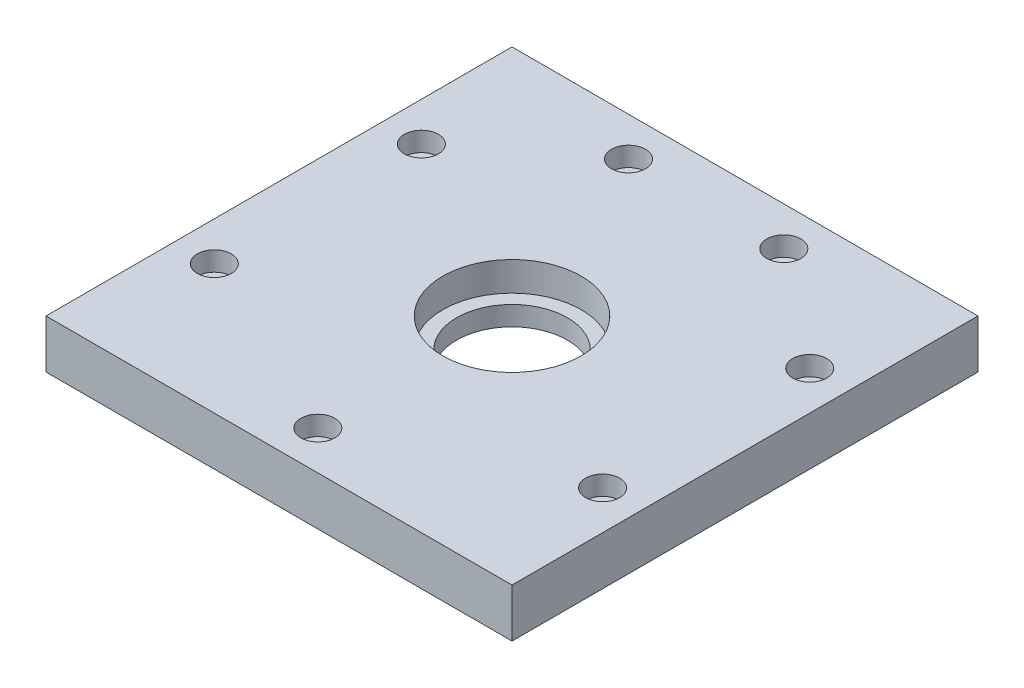
SolidWorks part; units mm, degrees
material "6061-O (SS)"
ref_plane "Front Plane" through (0, 0, 0) normal (0, 0, 1) x (1, 0, 0)
ref_plane "Top Plane" through (0, 0, 0) normal (0, 1, 0) x (1, 0, 0)
ref_plane "Right Plane" through (0, 0, 0) normal (1, 0, 0) x (0, 0, -1)
sketch "Sketch1" plane through (0, 0, 0) normal (0, 0, 1) x (1, 0, 0)
  line L7 (-76.2, -7.9375) -> (76.2, -7.9375)
  line L8 (-76.2, -7.9375) -> (-76.2, 7.9375)
  line L9 (-76.2, 7.9375) -> (76.2, 7.9375)
  line L10 (76.2, -7.9375) -> (76.2, 7.9375)
  line L11 (-76.2, -7.9375) -> (76.2, 7.9375) construction
  line L12 (-76.2, 7.9375) -> (76.2, -7.9375) construction
  point P4 (0, 0)
  point P14 (0, 0)
  dimension "Thickness" = 15.875
  dimension "Width" = 152.4
sketch "Sketch2" plane through (0, 0, 0) normal (0, 1, 0) x (0, 0, -1)
  line L0 (76.2, 76.2) -> (-76.2, 76.2) construction
  point P4 (0, 76.2)
  dimension "Length" = 152.4
sketch "Sketch3" plane through (0, 0, 0) normal (0, 0, 1) x (1, 0, 0)
  line L6 (-76.2, 7.9375) -> (76.2, 7.9375)
  line L7 (76.2, 7.9375) -> (76.2, -7.9375)
  line L8 (76.2, -7.9375) -> (-76.2, -7.9375)
  line L9 (-76.2, -7.9375) -> (-76.2, 7.9375)
extrude "Boss-Extrude1" add sketch "Sketch3" along normal mid plane 152.4
sketch "Sketch4" plane through (0, 7.9375, 0) normal (0, 1, 0) x (1, 0, 0)
  circle A0 centre (0, 0) radius 22.6219
  dimension "D1" = 45.2437
extrude "Cut-Extrude1" cut sketch "Sketch4" against normal blind 9.525
sketch "Sketch5" plane through (0, -1.5875, 0) normal (0, 1, 0) x (1, 0, 0)
  circle A0 centre (0, 0) radius 18.0975
  dimension "D1" = 36.195
extrude "Cut-Extrude2" cut sketch "Sketch5" against normal through all
sketch "Sketch6" plane through (0, 7.9375, 0) normal (0, 1, 0) x (1, 0, 0)
  line L2 (76.2, -76.2) -> (76.2, 76.2) construction
  line L3 (76.2, 76.2) -> (-76.2, 76.2) construction
  line L4 (-76.2, -76.2) -> (-76.2, 76.2) construction
  line L5 (76.2, -76.2) -> (-76.2, -76.2) construction
  point P0 (-25.4, 63.5)
  point P1 (-63.5, -33.8667)
  point P2 (-63.5, 33.8667)
  point P3 (25.4, 63.5)
  point P4 (63.5, 33.8667)
  point P5 (63.5, -33.8667)
  point P6 (0, -63.5)
  dimension "D1" = 12.7
  dimension "D2" = 42.3333
  dimension "D3" = 42.3333
  dimension "D4" = 50.8
  dimension "D5" = 50.8
  dimension "D6" = 12.7
  dimension "D7" = 12.7
  dimension "D8" = 12.7
hole_wizard "CBORE for 1/4 Socket Head Cap Screw1" positions "3DSketch1" profile "Sketch8" counterbore size "1/4" standard "ANSI Inch" end condition through all
sketch3d "3DSketch1"
  point P0 (-63.5, 7.9375, -33.8667)
  point P3 (-25.4, 7.9375, -63.5)
  point P6 (25.4, 7.9375, -63.5)
  point P9 (63.5, 7.9375, -33.8667)
  point P12 (63.5, 7.9375, 33.8667)
  point P15 (0, 7.9375, 63.5)
  point P18 (-63.5, 7.9375, 33.8667)
sketch "Sketch8" plane through (-63.5, 7.9375, -33.8667) normal (1, 0, 0) x (0, 0, 1)
  line L0 (0, 0) -> (0, 15.875)
  line L1 (0, 15.875) -> (3.3782, 15.875)
  line L3 (3.3782, 15.875) -> (3.3782, 6.35)
  line L4 (3.3782, 6.35) -> (5.5562, 6.35)
  line L5 (5.5562, 6.35) -> (5.5562, 0)
  line L7 (5.5562, 0) -> (0, 0)
  line L11 (0, -6.35) -> (0, 107.95) construction
  dimension "Thru Hole Dia." = 6.7564
  dimension "Thru Hole Depth" = 15.875
  dimension "C'Bore Dia." = 11.1125
  dimension "C'Bore Depth" = 6.35
equation "\"D1@Boss-Extrude1\" = \"Length@Sketch2\""
